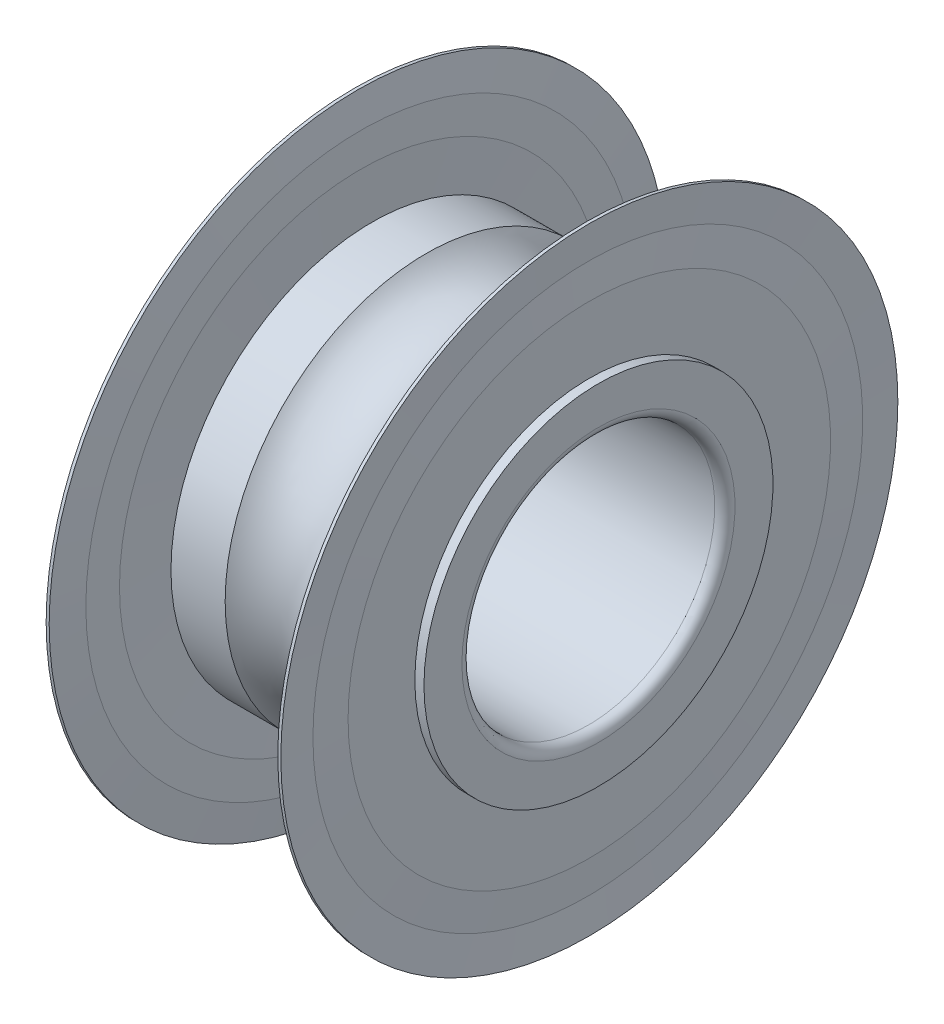
SolidWorks part; units mm, degrees
ref_plane "Front Plane" through (0, 0, 0) normal (0, 0, 1) x (1, 0, 0)
ref_plane "Top Plane" through (0, 0, 0) normal (0, 1, 0) x (1, 0, 0)
ref_plane "Right Plane" through (0, 0, 0) normal (1, 0, 0) x (0, 0, -1)
ref_plane "Plane1" through (0, 0, 0) normal (0, 0, 1) x (1, 0, 0)
sketch "Sketch1" plane through (0, 0, 0) normal (0, 0, 1) x (1, 0, 0)
  line L0 (0.2, 2.4998) -> (4.8, 2.4998)
  line L1 (5, 2.6998) -> (5, 3.976)
  line L2 (5, 3.976) -> (3.4046, 3.976)
  line L3 (1.5954, 3.976) -> (0, 3.976)
  line L4 (0, 3.976) -> (0, 2.6998)
  line L5 (50, 0) -> (-50, 0) construction
  arc A0 (0, 2.6998) -> (0.2, 2.4998) centre (0.2, 2.6998) ccw
  arc A1 (4.8, 2.4998) -> (5, 2.6998) centre (4.8, 2.6998) ccw
  arc A2 (3.4046, 3.976) -> (1.5954, 3.976) centre (2.5, 4.75) cw
revolve "Revolve1" add sketch "Sketch1" angle 360 about L5
ref_plane "Plane2" through (0, 0, 0) normal (0, 0, 1) x (1, 0, 0)
sketch "Sketch2" plane through (0, 0, 0) normal (0, 0, 1) x (1, 0, 0)
  line L0 (0, 4.6375) -> (0, 3.45)
  line L1 (0, 3.45) -> (0.262, 3.45)
  line L2 (0.524, 3.712) -> (0.524, 4.1135)
  line L3 (0.524, 4.1135) -> (4.476, 4.1135)
  line L4 (4.476, 4.1135) -> (4.476, 3.712)
  line L5 (4.738, 3.45) -> (5, 3.45)
  line L6 (5, 3.45) -> (5, 4.6375)
  line L7 (5, 4.6375) -> (0, 4.6375)
  line L8 (50, 0) -> (-50, 0) construction
  arc A0 (0.262, 3.45) -> (0.524, 3.712) centre (0.262, 3.712) ccw
  arc A1 (4.476, 3.712) -> (4.738, 3.45) centre (4.738, 3.712) ccw
revolve "Cut-Revolve1" cut sketch "Sketch2" angle 360 about L8
ref_plane "Plane3" through (0, 0, 0) normal (0, 0, 1) x (1, 0, 0)
sketch "Sketch3" plane through (0, 0, 0) normal (0, 0, 1) x (1, 0, 0)
  line L0 (0.18, 6.1) -> (0.21, 5.435)
  line L1 (0.21, 5.435) -> (0.18, 4.77)
  line L2 (0.18, 4.77) -> (0.18, 3.44)
  line L3 (0.18, 3.44) -> (0.24, 3.44)
  line L4 (0.24, 3.44) -> (0.3, 4.77)
  line L5 (0.3, 4.77) -> (0.3, 5.435)
  line L6 (0.3, 5.435) -> (0.24, 6.1)
  line L7 (0.24, 6.1) -> (0.18, 6.1)
  line L8 (50, 0) -> (-50, 0) construction
revolve "Revolve2" add sketch "Sketch3" angle 360 about L8
ref_plane "Plane4" through (0, 0, 0) normal (0, 0, 1) x (1, 0, 0)
sketch "Sketch4" plane through (0, 0, 0) normal (0, 0, 1) x (1, 0, 0)
  line L0 (4.7, 5.435) -> (4.7, 4.77)
  line L1 (4.7, 4.77) -> (4.76, 3.44)
  line L2 (4.76, 3.44) -> (4.82, 3.44)
  line L3 (4.82, 3.44) -> (4.82, 4.77)
  line L4 (4.82, 4.77) -> (4.79, 5.435)
  line L5 (4.79, 5.435) -> (4.82, 6.1)
  line L6 (4.82, 6.1) -> (4.76, 6.1)
  line L7 (4.76, 6.1) -> (4.7, 5.435)
  line L8 (50, 0) -> (-50, 0) construction
revolve "Revolve3" add sketch "Sketch4" angle 360 about L8
